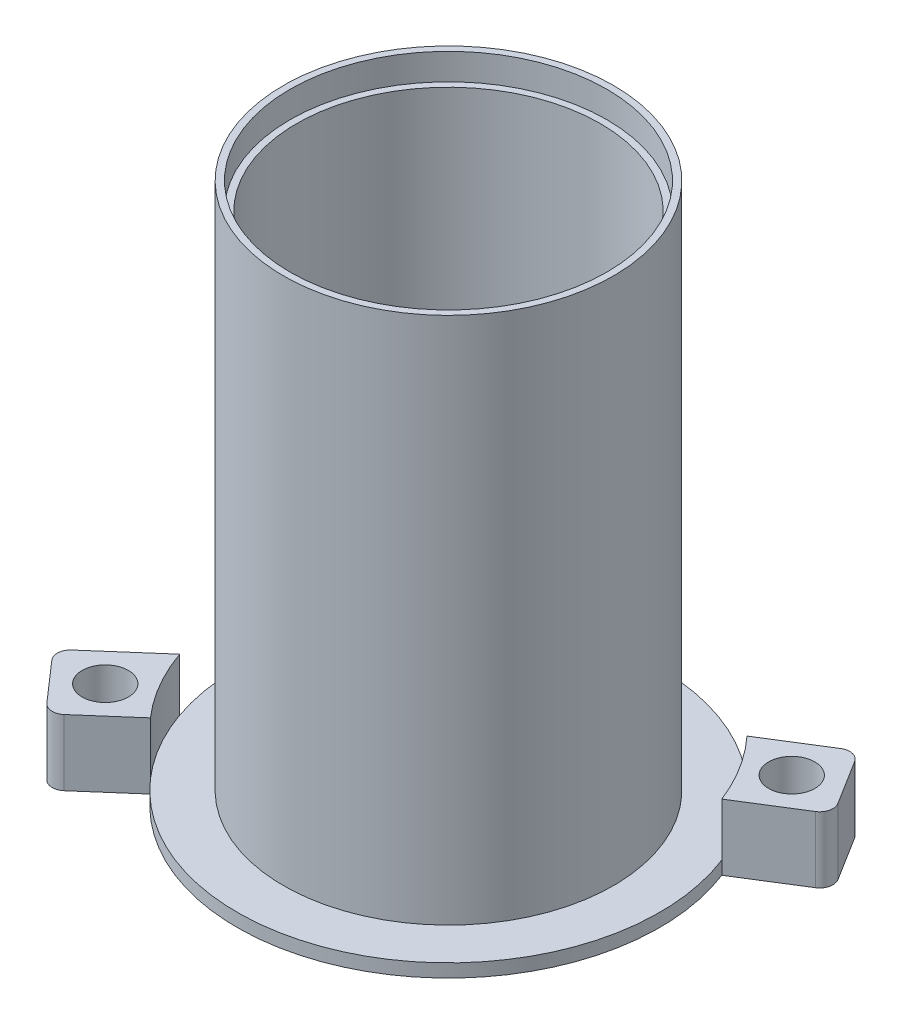
SolidWorks part; units mm, degrees
ref_plane "Front Plane" through (0, 0, 0) normal (0, 0, 1) x (1, 0, 0)
ref_plane "Top Plane" through (0, 0, 0) normal (0, 1, 0) x (1, 0, 0)
ref_plane "Right Plane" through (0, 0, 0) normal (1, 0, 0) x (0, 0, -1)
sketch "Sketch1" plane through (0, 0, 0) normal (0, 0, 1) x (1, 0, 0)
  line L8 (0, 0) -> (0, 36.8292) construction
  line L9 (-11.5, 0) -> (-16, 0)
  line L10 (-16, 0) -> (-16, 1)
  line L11 (-16, 1) -> (-12.5, 1)
  line L12 (-12.5, 1) -> (-12.5, 41)
  line L16 (-11.5, 39) -> (-11.5, 0)
  line L17 (-12.5, 41) -> (-12, 41)
  line L18 (-12, 41) -> (-12, 39)
  line L19 (-12, 39) -> (-11.5, 39)
  dimension "D1" = 11.5
  dimension "D2" = 4.5
  dimension "D3" = 1
  dimension "D4" = 40
  dimension "D5" = 0.5
  dimension "D6" = 2
  dimension "D7" = 1
revolve "Revolve1" add sketch "Sketch1" angle 360 about L8
sketch "Sketch2" plane through (0, 0, 0) normal (0, -1, 0) x (1, 0, 0)
  line L0 (14.9173, -5.7856) -> (20.134, -9.046)
  line L1 (0, 0) -> (-16, 0) construction
  line L2 (0, 0) -> (0, 10) construction
  line L3 (0, 10) -> (-16, 10) construction
  line L4 (-16, 0) -> (-16, 10) construction
  line L5 (0, 0) -> (16, 0) construction
  line L6 (0, 0) -> (0, -10) construction
  line L7 (0, -10) -> (16, -10) construction
  line L8 (16, 0) -> (16, -10) construction
  line L9 (20.134, -9.046) -> (16.954, -14.134)
  line L10 (16.954, -14.134) -> (11.7373, -10.8736)
  line L11 (-12.0471, 10.5294) -> (-16.2846, 14.2331)
  line L12 (-16.2846, 14.2331) -> (-20.2331, 9.7154)
  line L13 (-20.2331, 9.7154) -> (-15.1164, 5.2434)
  circle A0 centre (-16, 10) radius 1.75
  circle A1 centre (16, -10) radius 1.75
  circle A2 centre (0, 0) radius 16 construction
  circle A3 centre (0, 0) radius 16 construction
  dimension "D3" = 3.5
  dimension "D1" = 10
  dimension "D2" = 16
  dimension "D4" = 3
  dimension "D5" = 3
  dimension "D6" = 3
  dimension "D7" = 6
  dimension "D8" = 3
  dimension "D9" = 3
  dimension "D10" = 3
extrude "Boss-Extrude1" add sketch "Sketch2" against normal blind 5 contours L12 L13 L11 A0 | L10 L9 L0 L13 A1
fillet "Fillet1" radius 1 4 edges at (20.134, 2.5, -9.046) (16.954, 2.5, -14.134) (-16.2846, 2.5, 14.2331) (-20.2331, 2.5, 9.7154)
